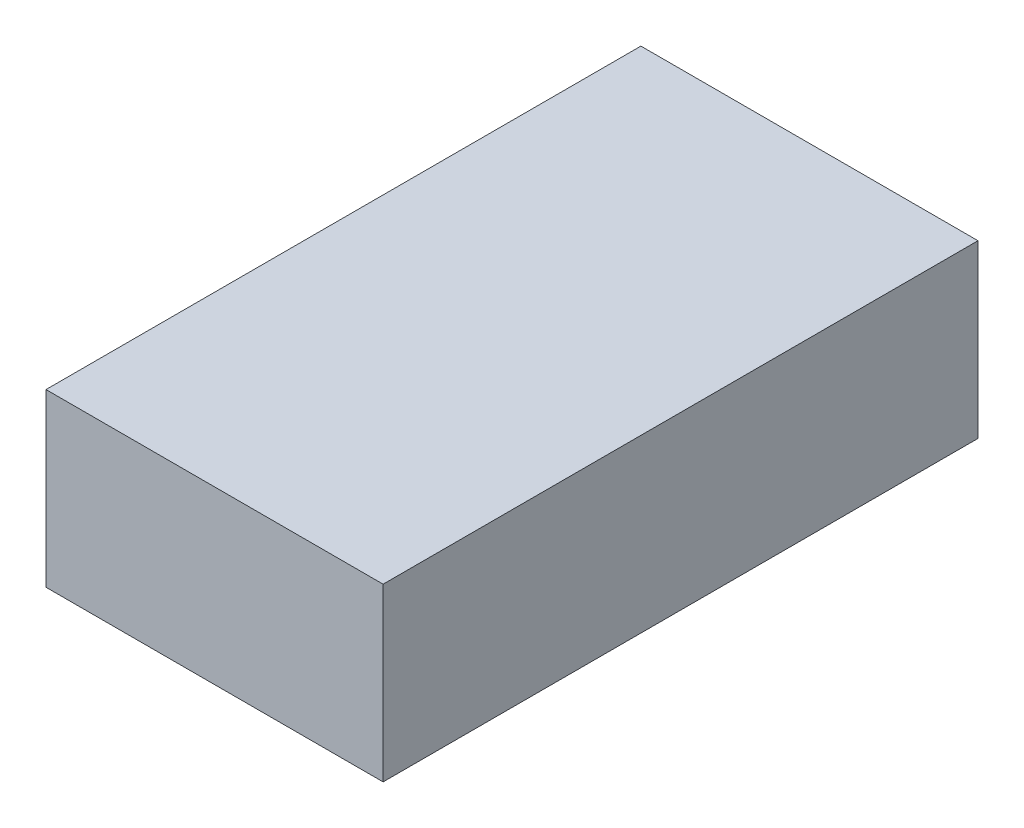
SolidWorks part; units mm, degrees
ref_plane "Front Plane" through (0, 0, 0) normal (0, 0, 1) x (1, 0, 0)
ref_plane "Top Plane" through (0, 0, 0) normal (0, 1, 0) x (1, 0, 0)
ref_plane "Right Plane" through (0, 0, 0) normal (1, 0, 0) x (0, 0, -1)
sketch "Sketch1" plane through (0, 0, 0) normal (0, 1, 0) x (1, 0, 0)
  line L1 (-42.5, -75) -> (42.5, -75)
  line L2 (-42.5, -75) -> (-42.5, 75)
  line L3 (-42.5, 75) -> (42.5, 75)
  line L4 (42.5, -75) -> (42.5, 75)
  line L5 (-42.5, -75) -> (42.5, 75) construction
  line L6 (-42.5, 75) -> (42.5, -75) construction
  point P0 (0, 0)
  dimension "D1" = 150
  dimension "D2" = 85
extrude "Boss-Extrude1" add sketch "Sketch1" along normal blind 43.18
